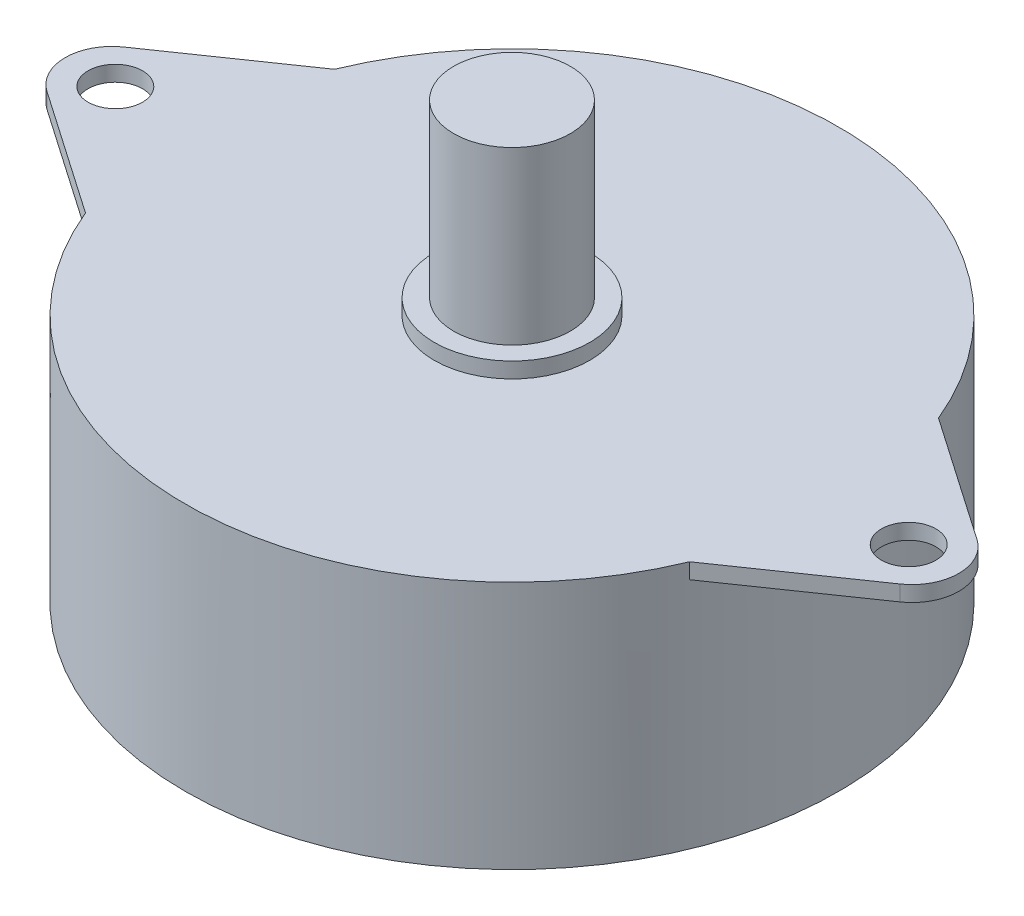
SolidWorks part; units mm, degrees
ref_plane "Front Plane" through (0, 0, 0) normal (0, 0, 1) x (1, 0, 0)
ref_plane "Top Plane" through (0, 0, 0) normal (0, 1, 0) x (1, 0, 0)
ref_plane "Right Plane" through (0, 0, 0) normal (1, 0, 0) x (0, 0, -1)
sketch "Sketch1" plane through (0, 0, 0) normal (0, 1, 0) x (1, 0, 0)
  circle A0 centre (0, 0) radius 21
  dimension "D1" = 42
extrude "Extrude1" add sketch "Sketch1" along normal blind 16
sketch "Sketch5" plane through (0, 16, 0) normal (0, 1, 0) x (-1, 0, 0)
  line L1 (19.4165, 8) -> (27.4258, 2.4685)
  line L2 (27.4258, -2.4685) -> (19.4165, -8)
  line L3 (19.4165, -8) -> (-19.4165, -8)
  line L4 (-19.4165, -8) -> (-27.4258, -2.4685)
  line L5 (-27.4258, 2.4685) -> (-19.4165, 8)
  line L6 (-19.4165, 8) -> (19.4165, 8)
  circle A0 centre (0, 0) radius 21 construction
  circle A1 centre (25.5, 0) radius 1.75
  circle A2 centre (-25.5, 0) radius 1.75
  arc A3 (27.4258, -2.4685) -> (27.4258, 2.4685) centre (25.7209, 0) ccw
  arc A4 (-27.4258, -2.4685) -> (-27.4258, 2.4685) centre (-25.7209, 0) cw
  point P15 (31, 0)
  point P18 (-31, 0)
  dimension "D7" = 3.5
  dimension "D8" = 3.5
  dimension "D11" = 3
  dimension "D1" = 8
  dimension "D2" = 8
  dimension "D3" = 8
  dimension "D4" = 8
  dimension "D5" = 31
  dimension "D6" = 31
  dimension "D9" = 25.5
  dimension "D10" = 25.5
extrude "Extrude2" add sketch "Sketch5" against normal blind 1
sketch "Sketch6" plane through (0, 16, 0) normal (0, 1, 0) x (-1, 0, 0)
  circle A0 centre (0, 0) radius 5
  dimension "D1" = 10
extrude "Extrude3" add sketch "Sketch6" along normal blind 1
sketch "Sketch7" plane through (0, 17, 0) normal (0, 1, 0) x (-1, 0, 0)
  circle A0 centre (0, 0) radius 3.75
  point P3 (1.5917, 3.0547)
extrude "Extrude4" add sketch "Sketch7" along normal blind 11
